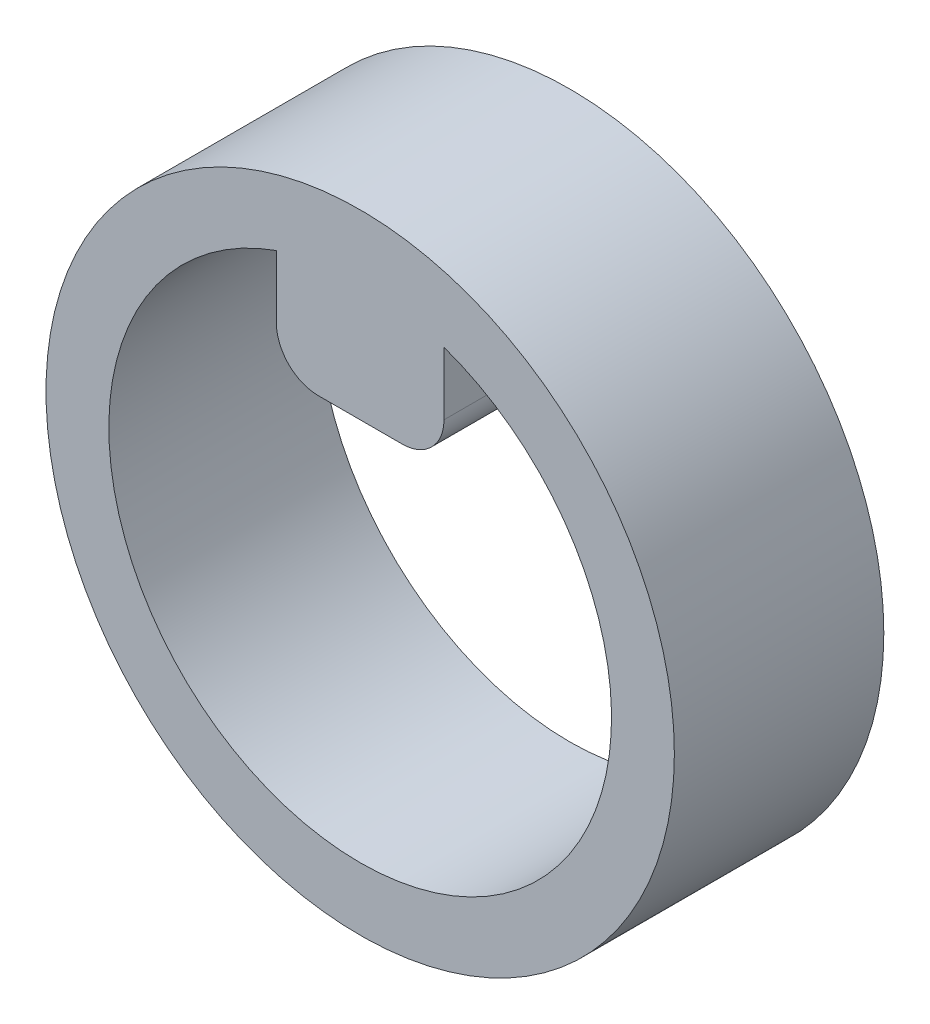
SolidWorks part; units mm, degrees
ref_plane "Front Plane" through (0, 0, 0) normal (0, 0, 1) x (1, 0, 0)
ref_plane "Top Plane" through (0, 0, 0) normal (0, 1, 0) x (1, 0, 0)
ref_plane "Right Plane" through (0, 0, 0) normal (1, 0, 0) x (0, 0, -1)
sketch "Sketch2" plane through (0, 0, 0) normal (0, 0, 1) x (1, 0, 0)
  line L0 (-2, 3.1569) -> (2, 3.1569)
  line L1 (-2, 3.1569) -> (-2, 5.6569)
  line L2 (2, 3.1569) -> (2, 5.6569)
  arc A0 (-2, 5.6569) -> (2, 5.6569) centre (0, 0) ccw
  circle A1 centre (0, 0) radius 7.5
  dimension "D1" = 12
  dimension "D2" = 15
  dimension "D3" = 2
  dimension "D4" = 4
  dimension "D5" = 2.5
extrude "Boss-Extrude1" add sketch "Sketch2" along normal blind 5
fillet "Fillet1" radius 1 2 edges at (-2, 3.1569, 2.5) (2, 3.1569, 2.5)
